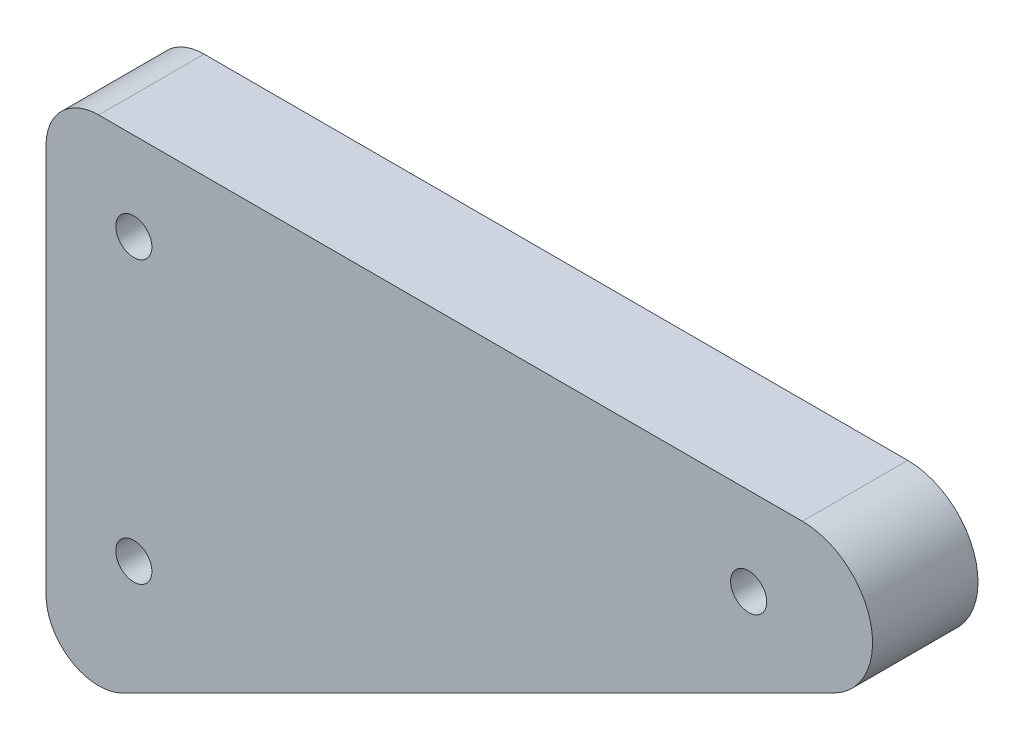
SolidWorks part; units mm, degrees
material "Acrylic (Medium-high impact)"
ref_plane "Front Plane" through (0, 0, 0) normal (0, 0, 1) x (1, 0, 0)
ref_plane "Top Plane" through (0, 0, 0) normal (0, 1, 0) x (1, 0, 0)
ref_plane "Right Plane" through (0, 0, 0) normal (1, 0, 0) x (0, 0, -1)
sketch "Sketch1" plane through (0, 0, 0) normal (0, 0, 1) x (1, 0, 0)
  line L0 (0, 0) -> (0, -47.625)
  line L1 (0, -55) -> (0, 55) construction
  line L2 (0, -47.625) -> (95.25, 0)
  line L3 (55, 0) -> (-55, 0) construction
  line L4 (95.25, 0) -> (0, 0)
  dimension "D1" = 95.25
  dimension "D2" = 47.625
extrude "Boss-Extrude1" add sketch "Sketch1" along normal mid plane 9.525
sketch "Sketch2" plane through (0, 0, 4.7625) normal (0, 0, 1) x (1, 0, 0)
  line L0 (7.9375, -7.9375) -> (7.9375, -33.3375) construction
  line L1 (7.9375, -7.9375) -> (63.5, -7.9375) construction
  line L2 (0, 0) -> (0, -47.625) construction
  line L3 (95.25, 0) -> (0, 0) construction
  dimension "D1" = 7.9375
  dimension "D2" = 7.9375
  dimension "D3" = 25.4
  dimension "D4" = 31.75
hole_wizard "#4 Clearance Hole1" positions "Sketch4" profile "Sketch3" hole size "#4" standard "Ansi Inch"
sketch "Sketch4" plane through (0, 0, 4.7625) normal (0, 0, 1) x (1, 0, 0)
  point P1 (7.9375, -7.9375)
  point P4 (63.5, -7.9375)
  point P7 (7.9375, -33.3375)
sketch "Sketch3" plane through (7.9375, -7.9375, 4.7625) normal (1, 0, 0) x (0, -1, 0)
  line L0 (0, 0) -> (0, 13.6806)
  line L1 (0, 13.6806) -> (1.6319, 12.7)
  line L2 (1.6319, 12.7) -> (1.6319, 0)
  line L5 (1.6319, 0) -> (0, 0)
  line L10 (0, 13.6806) -> (-1.632, 12.7) construction
  line L11 (0, -6.35) -> (0, 107.95) construction
  dimension "Hole Dia." = 3.2639
  dimension "Hole Depth" = 12.7
  dimension "Drill Angle" = 118
fillet "Fillet1" radius 4.7625 2 edges at (0, -47.625, 0) (0, 0, 0)
fillet "Fillet2" radius 6.35 1 edges at (95.25, 0, 0)
